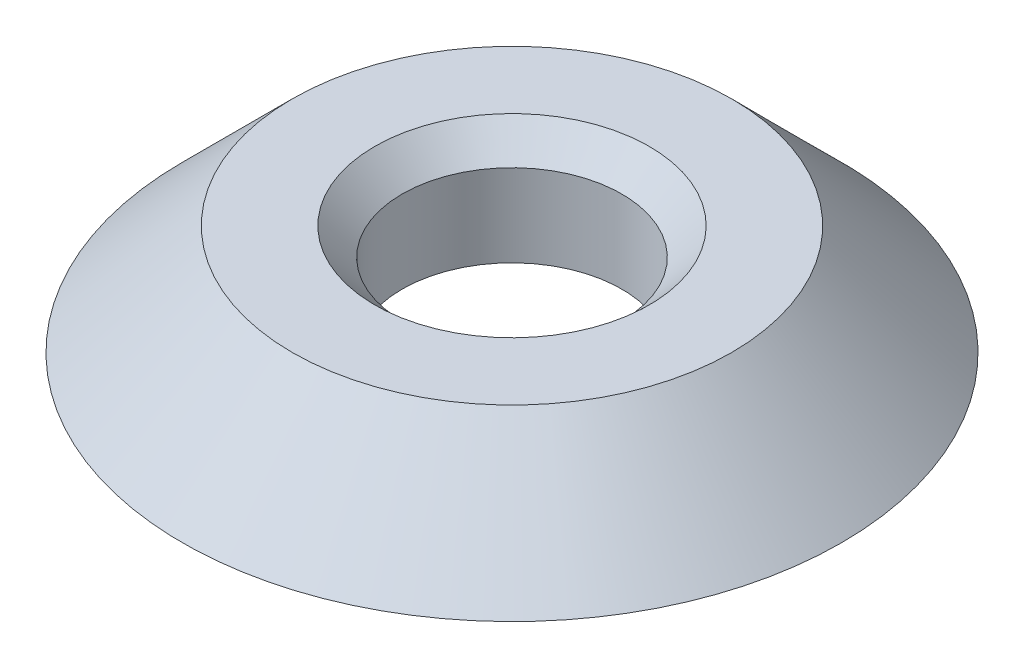
SolidWorks part; units mm, degrees
ref_plane "Front Plane" through (0, 0, 0) normal (0, 0, 1) x (1, 0, 0)
ref_plane "Top Plane" through (0, 0, 0) normal (0, 1, 0) x (1, 0, 0)
ref_plane "Right Plane" through (0, 0, 0) normal (1, 0, 0) x (0, 0, -1)
sketch "Sketch1" plane through (0, 0, 0) normal (0, 0, 1) x (1, 0, 0)
  line L0 (0, -795.7279) -> (0, 38990.6679) construction
  line L1 (2, 0) -> (2, 2)
  line L2 (2, 2) -> (4, 2)
  line L5 (4, 2) -> (6, 0)
  line L6 (6, 0) -> (2, 0)
  dimension "D1" = 4
  dimension "D2" = 8
  dimension "D3" = 12
  dimension "D5" = 2
revolve "Revolve1" add sketch "Sketch1" angle 360 about L0
chamfer "Chamfer1" distance 0.5 angle 45 1 edges at (2, 2, 0)
